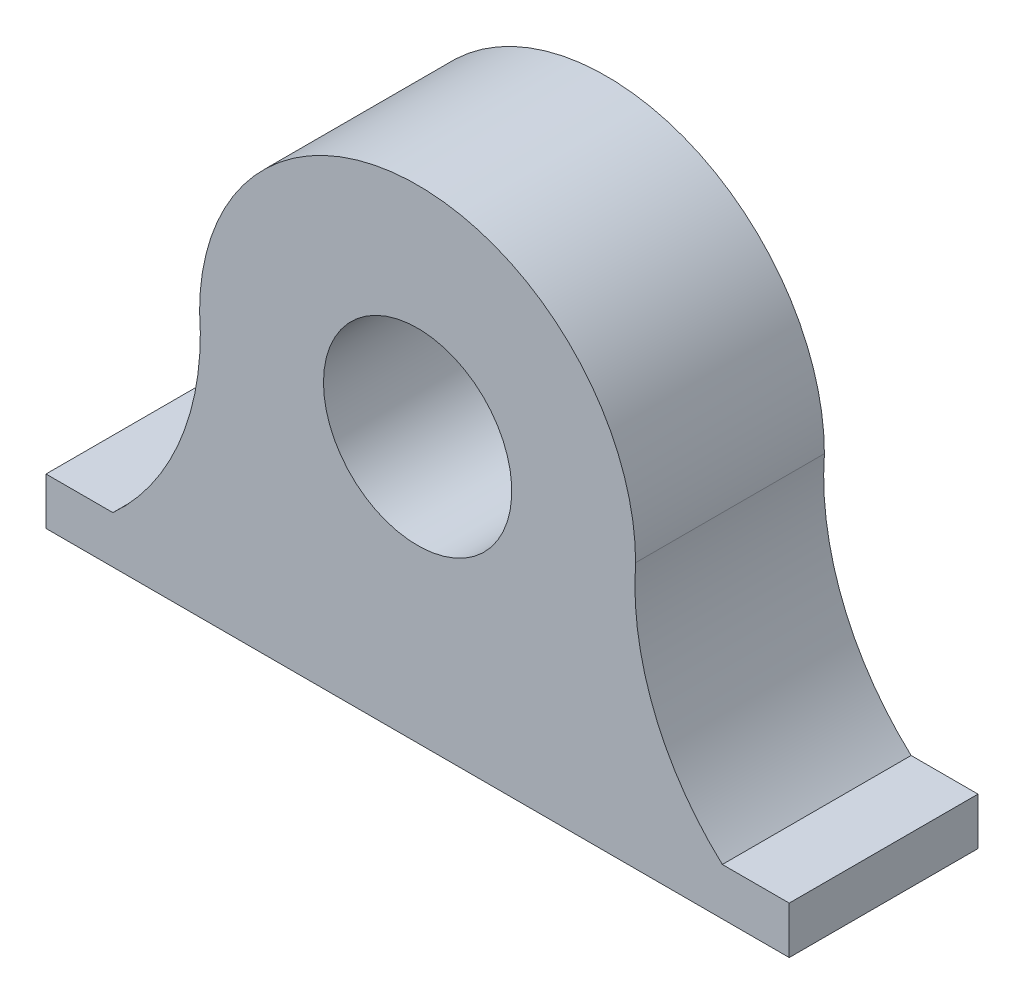
SolidWorks part; units mm, degrees
ref_plane "Alzado" through (0, 0, 0) normal (0, 0, 1) x (1, 0, 0)
ref_plane "Planta" through (0, 0, 0) normal (0, 1, 0) x (1, 0, 0)
ref_plane "Vista lateral" through (0, 0, 0) normal (1, 0, 0) x (0, 0, -1)
sketch "Croquis1" plane through (0, 0, 0) normal (0, 0, 1) x (1, 0, 0)
  line L0 (83.9232, -44) -> (61.5034, -44) construction
  line L1 (0, 31.8839) -> (0, -65.6426) construction
  line L2 (-75, -44) -> (-61.5034, -44)
  line L3 (-75, -44) -> (-75, -53.525)
  line L4 (-75, -53.525) -> (75, -53.525)
  line L5 (75, -44) -> (75, -53.525)
  line L6 (-61.5034, -44) -> (-96.8998, -44) construction
  line L7 (61.5034, -44) -> (75, -44)
  circle A0 centre (0, 0) radius 19
  arc A1 (43.8536, -3.5859) -> (-43.8536, -3.5859) centre (0, 0) ccw
  arc A2 (-61.5034, -44) -> (-44, 0) centre (-98, -4) ccw
  arc A3 (61.5034, -44) -> (44, 0) centre (98, -4) cw
  circle A4 centre (0, 0) radius 44 construction
  point P16 (0, 0)
  point P17 (-92.2741, -25.0777)
  point P18 (0, 0)
  point P19 (0, 0)
  point P20 (-61.6786, -44)
  dimension "D1" = 38
  dimension "D3" = 150
  dimension "D4" = 40
  dimension "D5" = 98
  dimension "D6" = 9.525
  dimension "D2" = 25
extrude "Saliente-Extruir1" add sketch "Croquis1" along normal blind 38.1 contours L7 A3 A1 A2 L2 L3 L4 L5 A0
